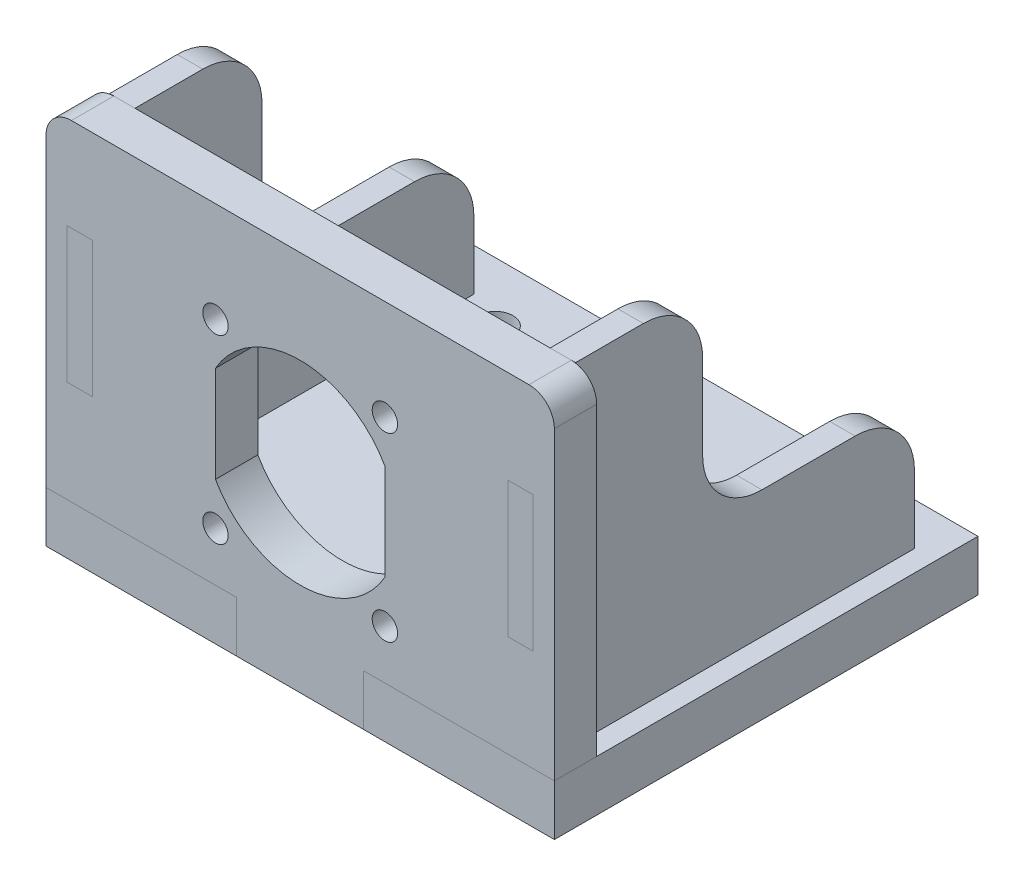
SolidWorks part; units mm, degrees
ref_plane "Front Plane" through (0, 0, 0) normal (0, 0, 1) x (1, 0, 0)
ref_plane "Top Plane" through (0, 0, 0) normal (0, 1, 0) x (1, 0, 0)
ref_plane "Right Plane" through (0, 0, 0) normal (1, 0, 0) x (0, 0, -1)
sketch "Sketch1" plane through (0, 0, 0) normal (0, 1, 0) x (1, 0, 0)
  line L0 (0, 0) -> (0, 50)
  line L1 (0, 50) -> (60, 50)
  line L2 (60, 50) -> (60, 0)
  line L3 (60, 0) -> (37.5, 0)
  line L4 (30, 0) -> (30, 50) construction
  line L5 (22.5, 0) -> (22.5, 5)
  line L6 (37.5, 0) -> (37.5, 5)
  line L7 (22.5, 5) -> (37.5, 5)
  line L8 (22.5, 0) -> (0, 0)
  line L9 (2.5, 18) -> (2.5, 34)
  line L10 (2.5, 34) -> (5.5, 34)
  line L11 (5.5, 34) -> (5.5, 18)
  line L12 (5.5, 18) -> (2.5, 18)
  line L13 (54.5, 34) -> (54.5, 18)
  line L14 (57.5, 34) -> (54.5, 34)
  line L15 (57.5, 18) -> (57.5, 34)
  line L16 (54.5, 18) -> (57.5, 18)
  line L17 (30, 25) -> (37.5, 25) construction
  circle A0 centre (10, 12) radius 2.1139
  circle A1 centre (50, 12) radius 2.1139
  circle A2 centre (50, 43) radius 2.1139
  circle A3 centre (10, 43) radius 2.1139
  point P29 (0, 0)
  dimension "D1" = 60
  dimension "D2" = 50
  dimension "D3" = 5
  dimension "D4" = 7.5
  dimension "D5" = 2.5
  dimension "D6" = 3
  dimension "D7" = 18
  dimension "D8" = 16
  dimension "D9" = 12
  dimension "D10" = 10
  dimension "D11" = 31
extrude "Base Part" add sketch "Sketch1" along normal blind 6
sketch "Sketch2" plane through (0, 0, 0) normal (0, 0, 1) x (1, 0, 0)
  line L0 (0, 6) -> (22.5, 6)
  line L1 (0, 6) -> (22.5, 6) construction
  line L2 (22.5, 6) -> (22.5, 0)
  line L3 (22.5, 0) -> (37.5, 0)
  line L4 (37.5, 0) -> (37.5, 6)
  line L5 (37.5, 6) -> (60, 6)
  line L6 (60, 6) -> (60, 42)
  line L7 (57, 45) -> (3, 45)
  line L8 (0, 42) -> (0, 6)
  line L9 (0, 0) -> (22.5, 0) construction
  line L10 (30, 45) -> (30, 0) construction
  line L11 (20, 28.1789) -> (20, 16.8211)
  line L12 (40, 28.1789) -> (40, 16.8211)
  line L13 (2.5, 34) -> (2.5, 18)
  line L14 (2.5, 18) -> (5.5, 18)
  line L15 (5.5, 18) -> (5.5, 34)
  line L16 (5.5, 34) -> (2.5, 34)
  line L17 (54.5, 18) -> (54.5, 34)
  line L18 (57.5, 18) -> (54.5, 18)
  line L19 (57.5, 34) -> (57.5, 18)
  line L20 (54.5, 34) -> (57.5, 34)
  line L21 (30, 22.5) -> (23.6184, 22.5) construction
  arc A0 (20, 16.8211) -> (40, 16.8211) centre (30, 22.5) ccw
  arc A1 (40, 28.1789) -> (20, 28.1789) centre (30, 22.5) ccw
  arc A2 (60, 42) -> (57, 45) centre (57, 42) ccw
  arc A3 (3, 45) -> (0, 42) centre (3, 42) ccw
  circle A4 centre (20, 33.1789) radius 1.5
  circle A5 centre (40, 33.1789) radius 1.5
  circle A6 centre (40, 11.8211) radius 1.5
  circle A7 centre (20, 11.8211) radius 1.5
  dimension "D2" = 23
  dimension "D9" = 3
  dimension "D10" = 3
  dimension "D1" = 45
  dimension "D3" = 20
  dimension "D4" = 11.3578
  dimension "D5" = 12
  dimension "D6" = 16
  dimension "D7" = 3
  dimension "D8" = 2.5
  dimension "D11" = 5
extrude "Vertical Part" add sketch "Sketch2" against normal blind 5 separate body
ref_plane "Plane1" through (2.5, 0, 0) normal (-1, 0, 0) x (0, 0, 1)
sketch "Sketch3" plane through (2.5, 0, 0) normal (-1, 0, 0) x (0, 0, 1)
  line L2 (-38, 21) -> (-27, 21)
  line L7 (-45, 6) -> (-45, 14)
  line L8 (-50, 6) -> (0, 6) construction
  line L10 (-20, 28) -> (-20, 38)
  line L18 (-5, 42) -> (-5, 6) construction
  line L19 (-13, 45) -> (-5, 45)
  line L20 (-5, 45) -> (-5, 34)
  line L21 (-5, 34) -> (0, 34)
  line L22 (0, 34) -> (0, 18)
  line L23 (0, 18) -> (-5, 18)
  line L24 (-5, 18) -> (-5, 6)
  line L25 (-5, 6) -> (-18, 6)
  line L26 (-34, 6) -> (-34, 0)
  line L27 (-34, 0) -> (-18, 0)
  line L28 (-18, 0) -> (-18, 6)
  line L29 (-34, 6) -> (-45, 6)
  arc A0 (-20, 38) -> (-13, 45) centre (-13, 38) cw
  arc A1 (-27, 21) -> (-20, 28) centre (-27, 28) ccw
  arc A2 (-45, 14) -> (-38, 21) centre (-38, 14) cw
  dimension "D1" = 40
  dimension "D2" = 15
  dimension "D3" = 15
extrude "Side Part" add sketch "Sketch3" against normal blind 3 separate body
ref_plane "Plane2" through (30, 0, 0) normal (-1, 0, 0) x (0, 0, 1)
pattern_linear "LPattern1" count 2 spacing 52 along (1, 0, 0) of "Side Part"
